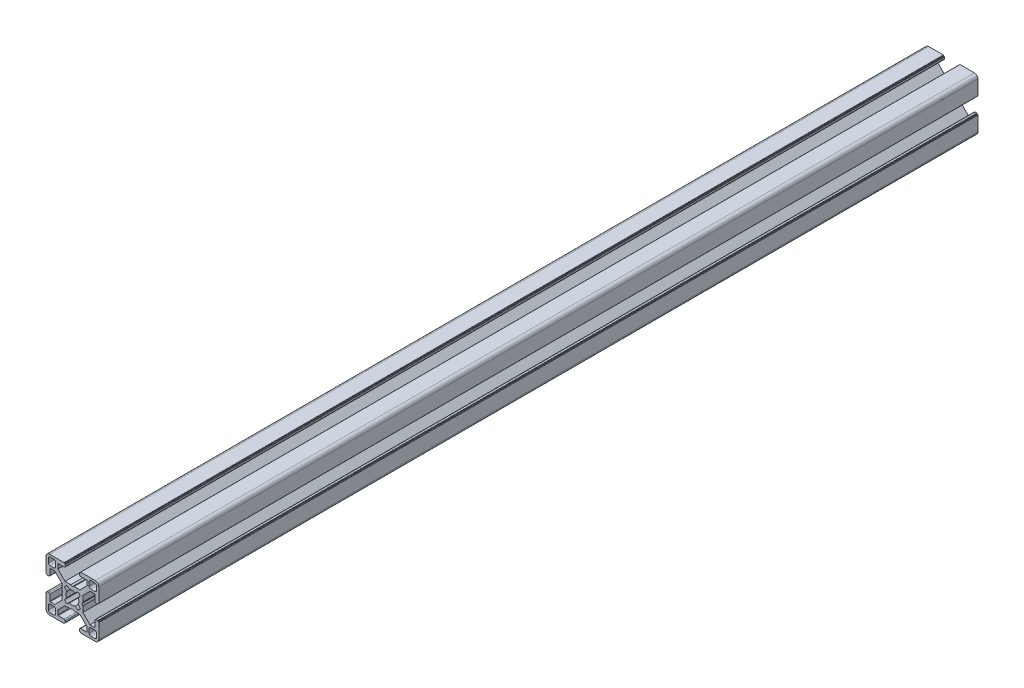
SolidWorks part; units mm, degrees
material "6061 Alloy"
ref_plane "Front" through (0, 0, 0) normal (0, 0, 1) x (1, 0, 0)
ref_plane "Top" through (0, 0, 0) normal (0, 1, 0) x (1, 0, 0)
ref_plane "Right" through (0, 0, 0) normal (1, 0, 0) x (0, 0, -1)
sketch "Sketch1" plane through (0, 0, 0) normal (0, 0, 1) x (1, 0, 0)
  line L0 (13.7, 12.7) -> (13.7, 10.5)
  line L1 (10.5, 9.5) -> (12.7, 9.5)
  line L2 (9.5, 12.7) -> (9.5, 10.5)
  line L3 (10.5, 13.7) -> (12.7, 13.7)
  line L4 (3.1359, 4.5184) -> (1.6001, 3.2806)
  line L5 (3.2806, 1.6001) -> (4.5053, 3.1547)
  line L6 (6.0045, 0.9) -> (5.4849, 0)
  line L7 (6.0045, 4.2045) -> (6.0045, 0.9)
  line L8 (0, -5.4849) -> (0.9, -6)
  line L9 (0.9, -6) -> (4.2045, -6)
  line L10 (4.2045, -6) -> (8.25, -10.05)
  line L11 (8.25, -10.05) -> (8.25, -12.6)
  line L12 (4.65, -12.8) -> (8.05, -12.8)
  line L13 (4.05, -14.3) -> (4.05, -13.4)
  line L14 (4.25, -14.5) -> (4.35, -14.5)
  line L15 (4.55, -14.8) -> (4.55, -14.7)
  line L16 (4.75, -15) -> (13, -15)
  line L17 (15, -13) -> (15, -4.75)
  line L18 (14.7, -4.55) -> (14.8, -4.55)
  line L19 (14.5, -4.35) -> (14.5, -4.25)
  line L20 (13.4, -4.05) -> (14.3, -4.05)
  line L21 (12.8, -8.05) -> (12.8, -4.65)
  line L22 (12.6, -8.25) -> (10.05, -8.25)
  line L23 (10.05, -8.25) -> (6.0045, -4.2045)
  line L24 (6.0045, -4.2045) -> (6.0045, -0.9)
  line L25 (6.0045, -0.9) -> (5.4849, 0)
  line L26 (10.05, 8.25) -> (6.0045, 4.2045)
  line L27 (12.6, 8.25) -> (10.05, 8.25)
  line L28 (12.8, 8.05) -> (12.8, 4.65)
  line L29 (13.4, 4.05) -> (14.3, 4.05)
  line L30 (14.5, 4.35) -> (14.5, 4.25)
  line L31 (14.7, 4.55) -> (14.8, 4.55)
  line L32 (15, 13) -> (15, 4.75)
  line L33 (4.75, 15) -> (13, 15)
  line L34 (4.55, 14.8) -> (4.55, 14.7)
  line L35 (4.25, 14.5) -> (4.35, 14.5)
  line L36 (4.05, 14.3) -> (4.05, 13.4)
  line L37 (4.65, 12.8) -> (8.05, 12.8)
  line L38 (8.25, 10.05) -> (8.25, 12.6)
  line L39 (4.2045, 6) -> (8.25, 10.05)
  line L40 (0.9, 6) -> (4.2045, 6)
  line L41 (0, 5.4849) -> (0.9, 6)
  line L42 (-13.7, -12.7) -> (-13.7, -10.5)
  line L43 (-10.5, -9.5) -> (-12.7, -9.5)
  line L44 (-9.5, -12.7) -> (-9.5, -10.5)
  line L45 (-10.5, -13.7) -> (-12.7, -13.7)
  line L46 (-3.1359, -4.5184) -> (-1.6001, -3.2806)
  line L47 (-3.2806, -1.6001) -> (-4.5053, -3.1547)
  line L48 (0, 5.4849) -> (-0.9, 6)
  line L49 (-0.9, 6) -> (-4.2045, 6)
  line L50 (-4.2045, 6) -> (-8.25, 10.05)
  line L51 (-8.25, 10.05) -> (-8.25, 12.6)
  line L52 (-4.65, 12.8) -> (-8.05, 12.8)
  line L53 (-4.05, 14.3) -> (-4.05, 13.4)
  line L54 (-4.25, 14.5) -> (-4.35, 14.5)
  line L55 (-4.55, 14.8) -> (-4.55, 14.7)
  line L56 (-4.75, 15) -> (-13, 15)
  line L57 (-15, 13) -> (-15, 4.75)
  line L58 (-14.7, 4.55) -> (-14.8, 4.55)
  line L59 (-14.5, 4.35) -> (-14.5, 4.25)
  line L60 (-13.4, 4.05) -> (-14.3, 4.05)
  line L61 (-12.8, 8.05) -> (-12.8, 4.65)
  line L62 (-12.6, 8.25) -> (-10.05, 8.25)
  line L63 (-10.05, 8.25) -> (-6.0045, 4.2045)
  line L64 (-6.0045, -0.9) -> (-5.4849, 0)
  line L65 (-6.0045, -4.2045) -> (-6.0045, -0.9)
  line L66 (-10.05, -8.25) -> (-6.0045, -4.2045)
  line L67 (-12.6, -8.25) -> (-10.05, -8.25)
  line L68 (-12.8, -8.05) -> (-12.8, -4.65)
  line L69 (-13.4, -4.05) -> (-14.3, -4.05)
  line L70 (-14.5, -4.35) -> (-14.5, -4.25)
  line L71 (-14.7, -4.55) -> (-14.8, -4.55)
  line L72 (-15, -13) -> (-15, -4.75)
  line L73 (-4.75, -15) -> (-13, -15)
  line L74 (-4.55, -14.8) -> (-4.55, -14.7)
  line L75 (-4.25, -14.5) -> (-4.35, -14.5)
  line L76 (-4.05, -14.3) -> (-4.05, -13.4)
  line L77 (3.2806, -1.6001) -> (4.5053, -3.1547)
  line L78 (3.1359, -4.5184) -> (1.6001, -3.2806)
  line L79 (-4.65, -12.8) -> (-8.05, -12.8)
  line L80 (-8.25, -10.05) -> (-8.25, -12.6)
  line L81 (-4.2045, -6) -> (-8.25, -10.05)
  line L82 (-0.9, -6) -> (-4.2045, -6)
  line L83 (0, -5.4849) -> (-0.9, -6)
  line L84 (10.5, -13.7) -> (12.7, -13.7)
  line L85 (9.5, -12.7) -> (9.5, -10.5)
  line L86 (10.5, -9.5) -> (12.7, -9.5)
  line L87 (13.7, -12.7) -> (13.7, -10.5)
  line L88 (-6.0045, 4.2045) -> (-6.0045, 0.9)
  line L89 (-6.0045, 0.9) -> (-5.4849, 0)
  line L90 (-3.2806, 1.6001) -> (-4.5053, 3.1547)
  line L91 (-3.1359, 4.5184) -> (-1.6001, 3.2806)
  line L92 (-10.5, 13.7) -> (-12.7, 13.7)
  line L93 (-9.5, 12.7) -> (-9.5, 10.5)
  line L94 (-10.5, 9.5) -> (-12.7, 9.5)
  line L95 (-13.7, 12.7) -> (-13.7, 10.5)
  line L96 (-23.4857, 0) -> (20.9308, 0) construction
  line L97 (0, 17.9563) -> (0, -17.361) construction
  arc A0 (13.7, 12.7) -> (12.7, 13.7) centre (12.7, 12.7) ccw
  arc A1 (12.7, 9.5) -> (13.7, 10.5) centre (12.7, 10.5) ccw
  arc A2 (9.5, 10.5) -> (10.5, 9.5) centre (10.5, 10.5) ccw
  arc A3 (10.5, 13.7) -> (9.5, 12.7) centre (10.5, 12.7) ccw
  arc A4 (1.6001, 3.2806) -> (-1.6001, 3.2806) centre (0, 0) ccw
  arc A5 (8.25, -12.6) -> (8.05, -12.8) centre (8.05, -12.6) cw
  arc A6 (4.65, -12.8) -> (4.05, -13.4) centre (4.65, -13.4) ccw
  arc A7 (4.05, -14.3) -> (4.25, -14.5) centre (4.25, -14.3) ccw
  arc A8 (4.35, -14.5) -> (4.55, -14.7) centre (4.35, -14.7) cw
  arc A9 (4.55, -14.8) -> (4.75, -15) centre (4.75, -14.8) ccw
  arc A10 (13, -15) -> (15, -13) centre (13, -13) ccw
  arc A11 (15, -4.75) -> (14.8, -4.55) centre (14.8, -4.75) ccw
  arc A12 (14.7, -4.55) -> (14.5, -4.35) centre (14.7, -4.35) cw
  arc A13 (14.5, -4.25) -> (14.3, -4.05) centre (14.3, -4.25) ccw
  arc A14 (13.4, -4.05) -> (12.8, -4.65) centre (13.4, -4.65) ccw
  arc A15 (12.8, -8.05) -> (12.6, -8.25) centre (12.6, -8.05) cw
  arc A16 (4.5053, 3.1547) -> (3.1359, 4.5184) centre (0, 0) ccw
  arc A17 (12.8, 8.05) -> (12.6, 8.25) centre (12.6, 8.05) ccw
  arc A18 (13.4, 4.05) -> (12.8, 4.65) centre (13.4, 4.65) cw
  arc A19 (14.5, 4.25) -> (14.3, 4.05) centre (14.3, 4.25) cw
  arc A20 (14.7, 4.55) -> (14.5, 4.35) centre (14.7, 4.35) ccw
  arc A21 (15, 4.75) -> (14.8, 4.55) centre (14.8, 4.75) cw
  arc A22 (13, 15) -> (15, 13) centre (13, 13) cw
  arc A23 (4.55, 14.8) -> (4.75, 15) centre (4.75, 14.8) cw
  arc A24 (4.35, 14.5) -> (4.55, 14.7) centre (4.35, 14.7) ccw
  arc A25 (4.05, 14.3) -> (4.25, 14.5) centre (4.25, 14.3) cw
  arc A26 (4.65, 12.8) -> (4.05, 13.4) centre (4.65, 13.4) cw
  arc A27 (8.25, 12.6) -> (8.05, 12.8) centre (8.05, 12.6) ccw
  arc A28 (-13.7, -12.7) -> (-12.7, -13.7) centre (-12.7, -12.7) ccw
  arc A29 (-12.7, -9.5) -> (-13.7, -10.5) centre (-12.7, -10.5) ccw
  arc A30 (-9.5, -10.5) -> (-10.5, -9.5) centre (-10.5, -10.5) ccw
  arc A31 (-10.5, -13.7) -> (-9.5, -12.7) centre (-10.5, -12.7) ccw
  arc A32 (-4.5053, -3.1547) -> (-3.1359, -4.5184) centre (0, 0) ccw
  arc A33 (-3.2806, 1.6001) -> (-3.2806, -1.6001) centre (0, 0) ccw
  arc A34 (-8.25, 12.6) -> (-8.05, 12.8) centre (-8.05, 12.6) cw
  arc A35 (-4.65, 12.8) -> (-4.05, 13.4) centre (-4.65, 13.4) ccw
  arc A36 (-4.05, 14.3) -> (-4.25, 14.5) centre (-4.25, 14.3) ccw
  arc A37 (-4.35, 14.5) -> (-4.55, 14.7) centre (-4.35, 14.7) cw
  arc A38 (-4.55, 14.8) -> (-4.75, 15) centre (-4.75, 14.8) ccw
  arc A39 (-13, 15) -> (-15, 13) centre (-13, 13) ccw
  arc A40 (-15, 4.75) -> (-14.8, 4.55) centre (-14.8, 4.75) ccw
  arc A41 (-14.7, 4.55) -> (-14.5, 4.35) centre (-14.7, 4.35) cw
  arc A42 (-14.5, 4.25) -> (-14.3, 4.05) centre (-14.3, 4.25) ccw
  arc A43 (-13.4, 4.05) -> (-12.8, 4.65) centre (-13.4, 4.65) ccw
  arc A44 (-12.8, 8.05) -> (-12.6, 8.25) centre (-12.6, 8.05) cw
  arc A45 (-4.5053, 3.1547) -> (-3.1359, 4.5184) centre (0, 0) cw
  arc A46 (-12.8, -8.05) -> (-12.6, -8.25) centre (-12.6, -8.05) ccw
  arc A47 (-13.4, -4.05) -> (-12.8, -4.65) centre (-13.4, -4.65) cw
  arc A48 (-14.5, -4.25) -> (-14.3, -4.05) centre (-14.3, -4.25) cw
  arc A49 (3.2806, 1.6001) -> (3.2806, -1.6001) centre (0, 0) cw
  arc A50 (4.5053, -3.1547) -> (3.1359, -4.5184) centre (0, 0) cw
  arc A51 (1.6001, -3.2806) -> (-1.6001, -3.2806) centre (0, 0) cw
  arc A52 (-14.7, -4.55) -> (-14.5, -4.35) centre (-14.7, -4.35) ccw
  arc A53 (-15, -4.75) -> (-14.8, -4.55) centre (-14.8, -4.75) cw
  arc A54 (-13, -15) -> (-15, -13) centre (-13, -13) cw
  arc A55 (-4.55, -14.8) -> (-4.75, -15) centre (-4.75, -14.8) cw
  arc A56 (10.5, -13.7) -> (9.5, -12.7) centre (10.5, -12.7) cw
  arc A57 (9.5, -10.5) -> (10.5, -9.5) centre (10.5, -10.5) cw
  arc A58 (12.7, -9.5) -> (13.7, -10.5) centre (12.7, -10.5) cw
  arc A59 (13.7, -12.7) -> (12.7, -13.7) centre (12.7, -12.7) cw
  arc A60 (-4.35, -14.5) -> (-4.55, -14.7) centre (-4.35, -14.7) ccw
  arc A61 (-4.05, -14.3) -> (-4.25, -14.5) centre (-4.25, -14.3) cw
  arc A62 (-4.65, -12.8) -> (-4.05, -13.4) centre (-4.65, -13.4) cw
  arc A63 (-8.25, -12.6) -> (-8.05, -12.8) centre (-8.05, -12.6) ccw
  arc A64 (-10.5, 13.7) -> (-9.5, 12.7) centre (-10.5, 12.7) cw
  arc A65 (-9.5, 10.5) -> (-10.5, 9.5) centre (-10.5, 10.5) cw
  arc A66 (-12.7, 9.5) -> (-13.7, 10.5) centre (-12.7, 10.5) cw
  arc A67 (-13.7, 12.7) -> (-12.7, 13.7) centre (-12.7, 12.7) cw
  point P81 (15, 15)
  point P82 (0, 15)
  point P203 (0, -15)
  point P204 (15, -15)
  point P206 (0, 0)
  point P207 (15, 0)
  point P219 (-15, 0)
  point P220 (-15, -15)
  point P221 (-15, 15)
extrude "Base-Extrude" add sketch "Sketch1" against normal blind 500
